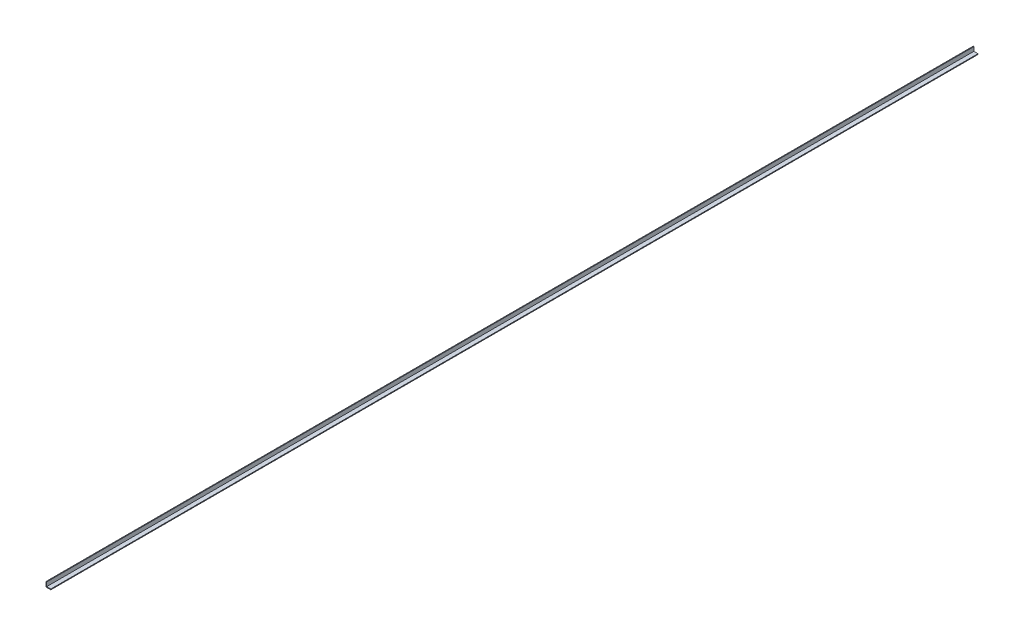
SolidWorks part; units mm, degrees
material "ASTM A36 Acero"
ref_plane "Alzado" through (0, 0, 0) normal (0, 0, 1) x (1, 0, 0)
ref_plane "Planta" through (0, 0, 0) normal (0, 1, 0) x (1, 0, 0)
ref_plane "Vista lateral" through (0, 0, 0) normal (1, 0, 0) x (0, 0, -1)
sketch "Croquis1" plane through (0, 0, 0) normal (0, 0, 1) x (1, 0, 0)
  line L0 (0, 31.75) -> (0, 0)
  line L1 (0, 0) -> (31.75, 0)
  line L2 (31.75, 0) -> (31.75, 4.76)
  line L3 (31.75, 4.76) -> (4.76, 4.76)
  line L4 (4.76, 4.76) -> (4.76, 31.75)
  line L5 (4.76, 31.75) -> (0, 31.75)
  dimension "D1" = 4.76
  dimension "D2" = 31.75
extrude "Saliente-Extruir1" add sketch "Croquis1" against normal blind 6100
